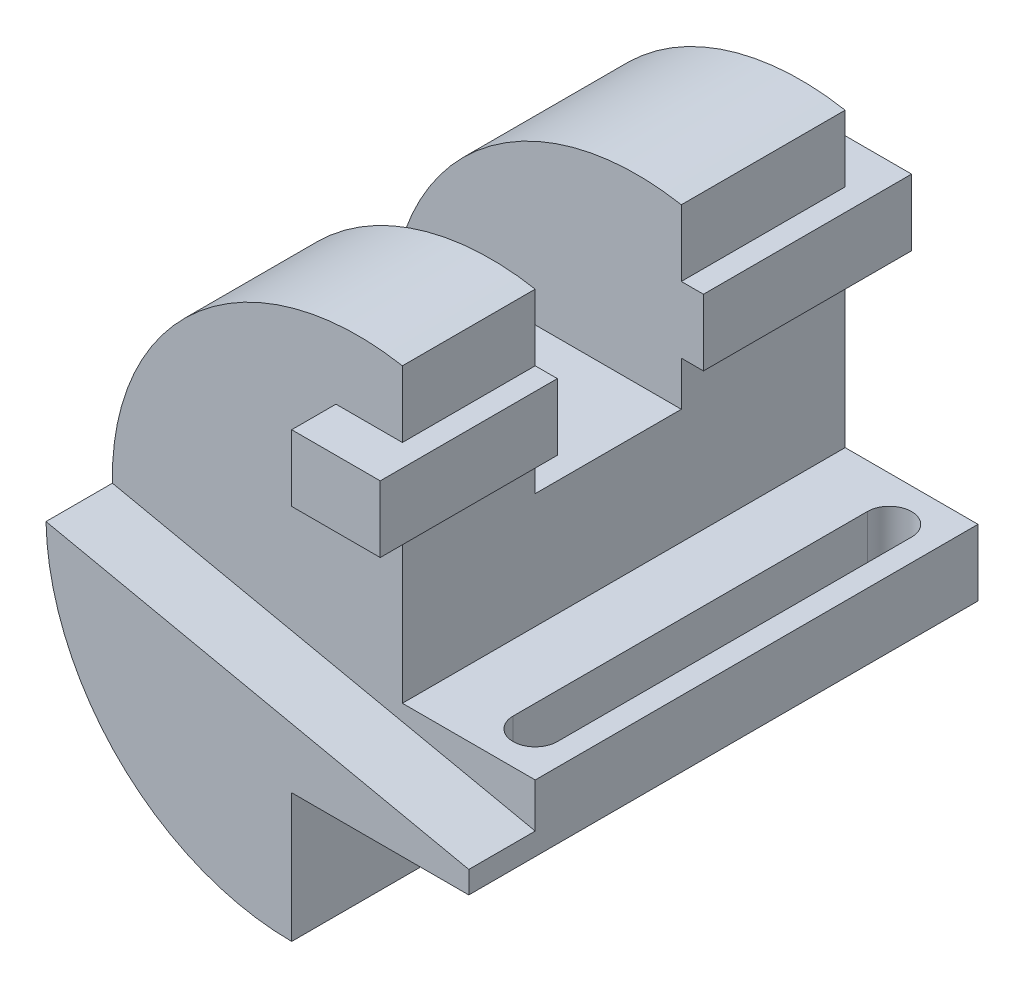
SolidWorks part; units mm, degrees
material "1060 Alloy"
ref_plane "Front Plane" through (0, 0, 0) normal (0, 0, 1) x (1, 0, 0)
ref_plane "Top Plane" through (0, 0, 0) normal (0, 1, 0) x (1, 0, 0)
ref_plane "Right Plane" through (0, 0, 0) normal (1, 0, 0) x (0, 0, -1)
sketch "Sketch1" plane through (0, 0, 0) normal (0, 0, 1) x (1, 0, 0)
  line L0 (0, 0) -> (-40, 0)
  line L1 (-40, 0) -> (-40, -29.0917)
  line L2 (0, 0) -> (0, 15)
  line L3 (0, 15) -> (-30, 15)
  line L4 (-30, 15) -> (-30, 81)
  arc A0 (-40, -29.0917) -> (-30, 81) centre (-40, 26.4083) cw
  point P8 (0, 0)
  point P9 (0, 0)
  dimension "D1" = 40
  dimension "D4" = 66
  dimension "D3" = 55.5
  dimension "D2" = 30
  dimension "D5" = 15
extrude "Boss-Extrude1" add sketch "Sketch1" along normal blind 115
sketch "Sketch2" plane through (0, 0, 115) normal (0, 0, 1) x (1, 0, 0)
  line L0 (0, 5) -> (-95.4889, 25.2968)
  line L1 (0, 0) -> (0, 15) construction
  line L2 (0, 15) -> (-30, 15) construction
  line L3 (-30, 15) -> (-30, 81) construction
  line L4 (0, 5) -> (0, 15)
  line L5 (0, 15) -> (-30, 15)
  line L6 (-30, 15) -> (-30, 81)
  arc A0 (-30, 81) -> (-40, -29.0917) centre (-40, 26.4083) ccw construction
  arc A1 (-30, 81) -> (-95.4889, 25.2968) centre (-40, 26.4083) ccw
  point P7 (-95.0422, 33.522)
  point P9 (0, 0)
  point P10 (0, 0)
  dimension "D1" = 5
  dimension "D2" = 78
extrude "Cut-Extrude1" cut sketch "Sketch2" against normal blind 15
sketch "Sketch3" plane through (0, 0, 0) normal (0, 0, -1) x (-1, 0, 0)
  line L0 (30, 15) -> (30, 81) construction
  line L1 (25, 66) -> (45, 66)
  line L2 (25, 66) -> (25, 51)
  line L3 (25, 51) -> (45, 51)
  line L4 (45, 66) -> (45, 51)
  dimension "D1" = 5
  dimension "D2" = 20
  dimension "D3" = 15
  dimension "D4" = 15
extrude "Boss-Extrude2" add sketch "Sketch3" against normal offset from surface 5 and the other way blind 10 up to face at (-37.3188, -2.0249, 115)
sketch "Sketch4" plane through (-30, 0, 0) normal (1, 0, 0) x (0, 0, -1)
  line L7 (0, 81.9083) -> (-100, 81.9083) construction
  line L8 (-70, 81.9083) -> (-37, 81.9083)
  line L9 (-70, 81.9083) -> (-70, 41)
  line L10 (-70, 41) -> (-37, 41)
  line L11 (-37, 81.9083) -> (-37, 41)
  line L12 (10, 51) -> (-110, 51) construction
  dimension "D1" = 30
  dimension "D2" = 33
  dimension "D3" = 10
extrude "Cut-Extrude4" cut sketch "Sketch4" against normal through all both and the other way through all
sketch "Sketch5" plane through (0, 15, 0) normal (0, 1, 0) x (1, 0, 0)
  line L0 (-10, -10) -> (-10, -90) construction
  line L1 (-5, -10) -> (-5, -90)
  line L2 (-15, -10) -> (-15, -90)
  line L3 (0, -100) -> (-30, -100) construction
  line L4 (0, -100) -> (0, 0) construction
  line L5 (0, 0) -> (-30, 0) construction
  arc A0 (-5, -10) -> (-15, -10) centre (-10, -10) ccw
  arc A1 (-15, -90) -> (-5, -90) centre (-10, -90) ccw
  point P2 (-10, -50)
  dimension "D1" = 80
  dimension "D2" = 10
  dimension "D3" = 10
  dimension "D4" = 10
  dimension "D5" = 10
extrude "Cut-Extrude5" cut sketch "Sketch5" against normal through all and the other way through all
equation "\"A\"= 55.50mm"
equation "\"B\"= 66mm"
equation "\"C\"= 33mm"
